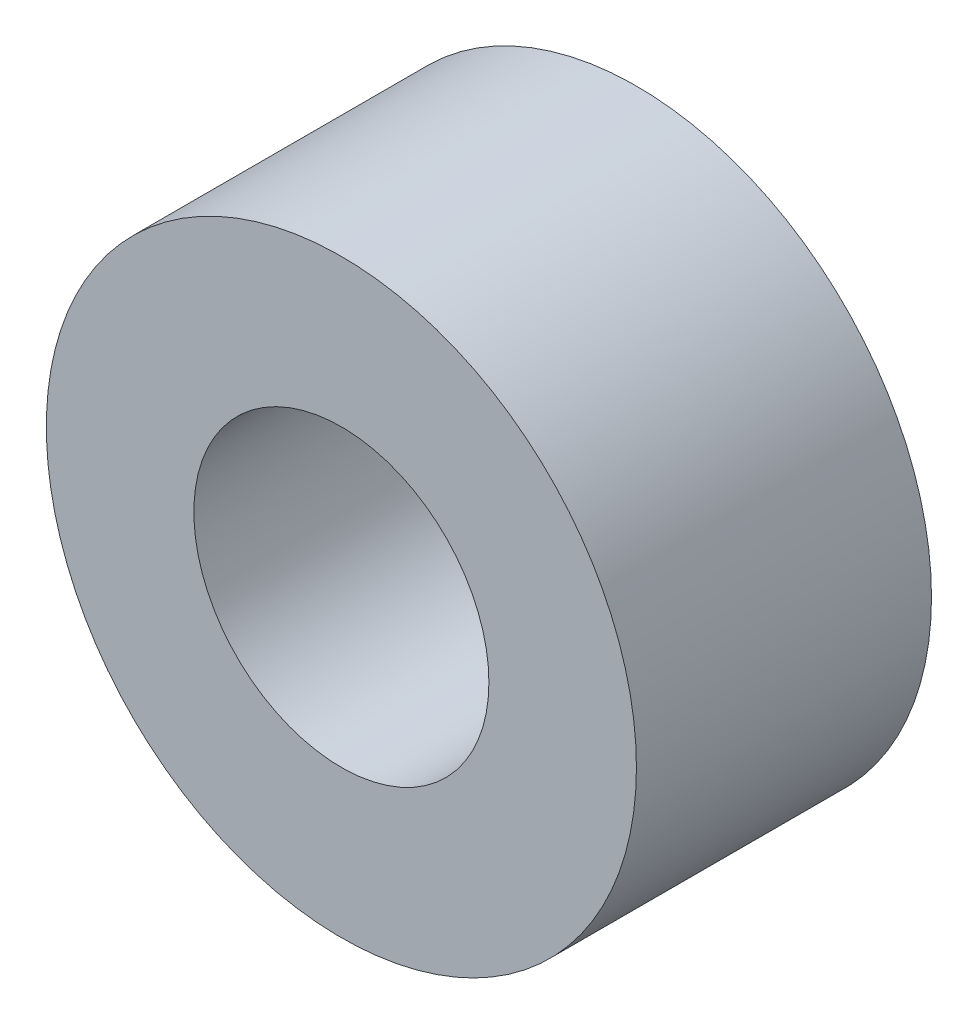
SolidWorks part; units mm, degrees
ref_plane "Front Plane" through (0, 0, 0) normal (0, 0, 1) x (1, 0, 0)
ref_plane "Top Plane" through (0, 0, 0) normal (0, 1, 0) x (1, 0, 0)
ref_plane "Right Plane" through (0, 0, 0) normal (1, 0, 0) x (0, 0, -1)
sketch "Sketch1" plane through (0, 0, 0) normal (0, 0, 1) x (1, 0, 0)
  circle A0 centre (0, 0) radius 2.5
  circle A1 centre (0, 0) radius 5
  dimension "D1" = 5
  dimension "D2" = 10
extrude "Boss-Extrude1" add sketch "Sketch1" along normal blind 5
